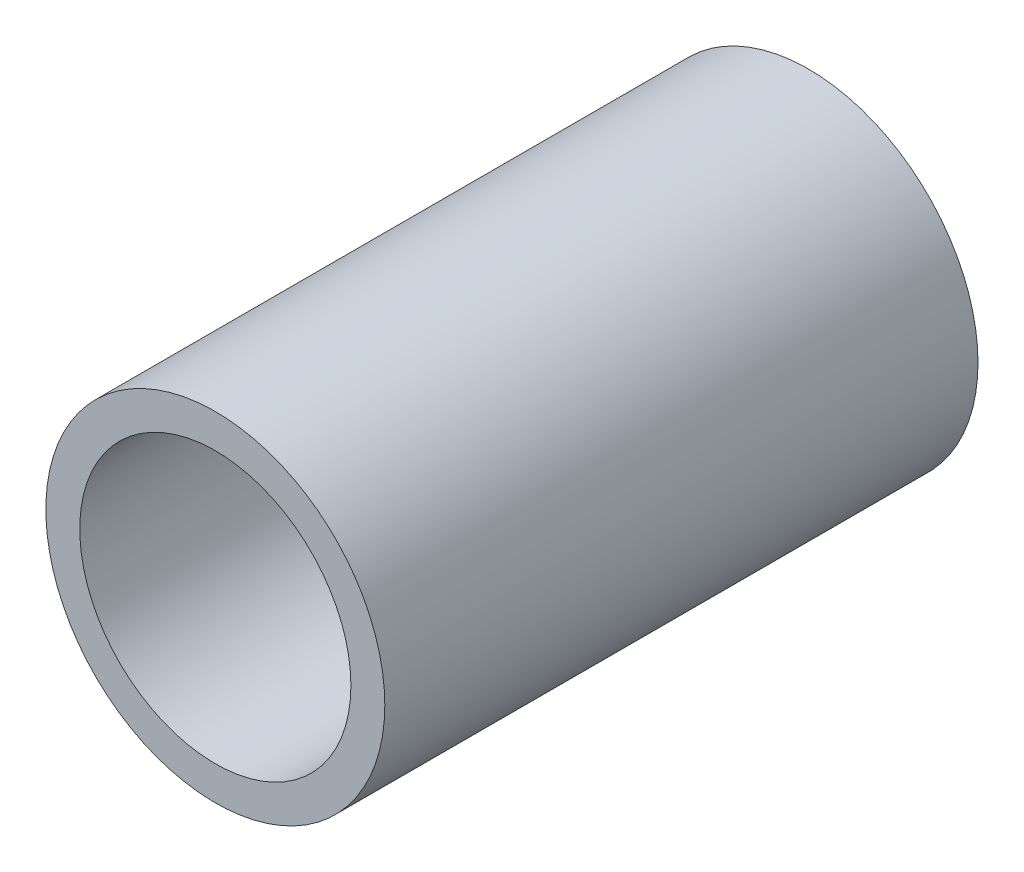
SolidWorks part; units mm, degrees
ref_plane "Front Plane" through (0, 0, 0) normal (0, 0, 1) x (1, 0, 0)
ref_plane "Top Plane" through (0, 0, 0) normal (0, 1, 0) x (1, 0, 0)
ref_plane "Right Plane" through (0, 0, 0) normal (1, 0, 0) x (0, 0, -1)
sketch "Sketch1" plane through (0, 0, 0) normal (0, 0, 1) x (1, 0, 0)
  circle A0 centre (0, 0) radius 4
  circle A1 centre (0, 0) radius 5
  dimension "D1" = 8
  dimension "D2" = 10
extrude "Boss-Extrude1" add sketch "Sketch1" along normal blind 17.5
